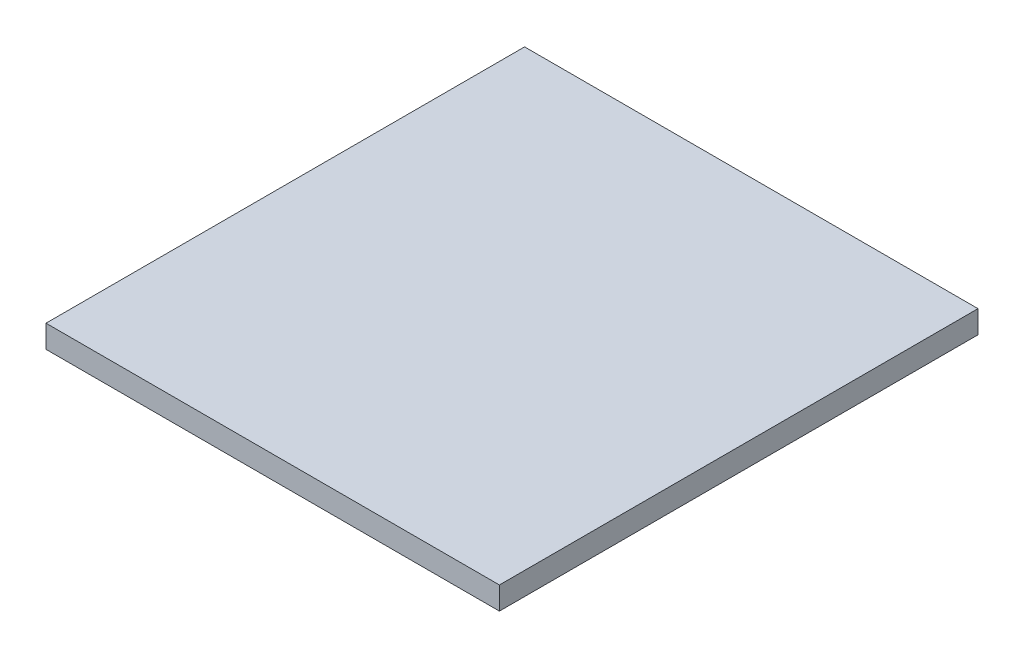
SolidWorks part; units mm, degrees
ref_plane "Alzado" through (0, 0, 0) normal (0, 0, 1) x (1, 0, 0)
ref_plane "Planta" through (0, 0, 0) normal (0, 1, 0) x (1, 0, 0)
ref_plane "Vista lateral" through (0, 0, 0) normal (1, 0, 0) x (0, 0, -1)
sketch "Croquis1" plane through (0, 0, 0) normal (0, 1, 0) x (1, 0, 0)
  line L1 (-180, 190) -> (180, 190)
  line L2 (-180, 190) -> (-180, -190)
  line L3 (-180, -190) -> (180, -190)
  line L4 (180, 190) -> (180, -190)
  line L5 (-180, 190) -> (180, -190) construction
  line L6 (-180, -190) -> (180, 190) construction
  point P0 (0, 0)
  dimension "D1" = 360
  dimension "D2" = 380
extrude "Saliente-Extruir1" add sketch "Croquis1" along normal blind 18
